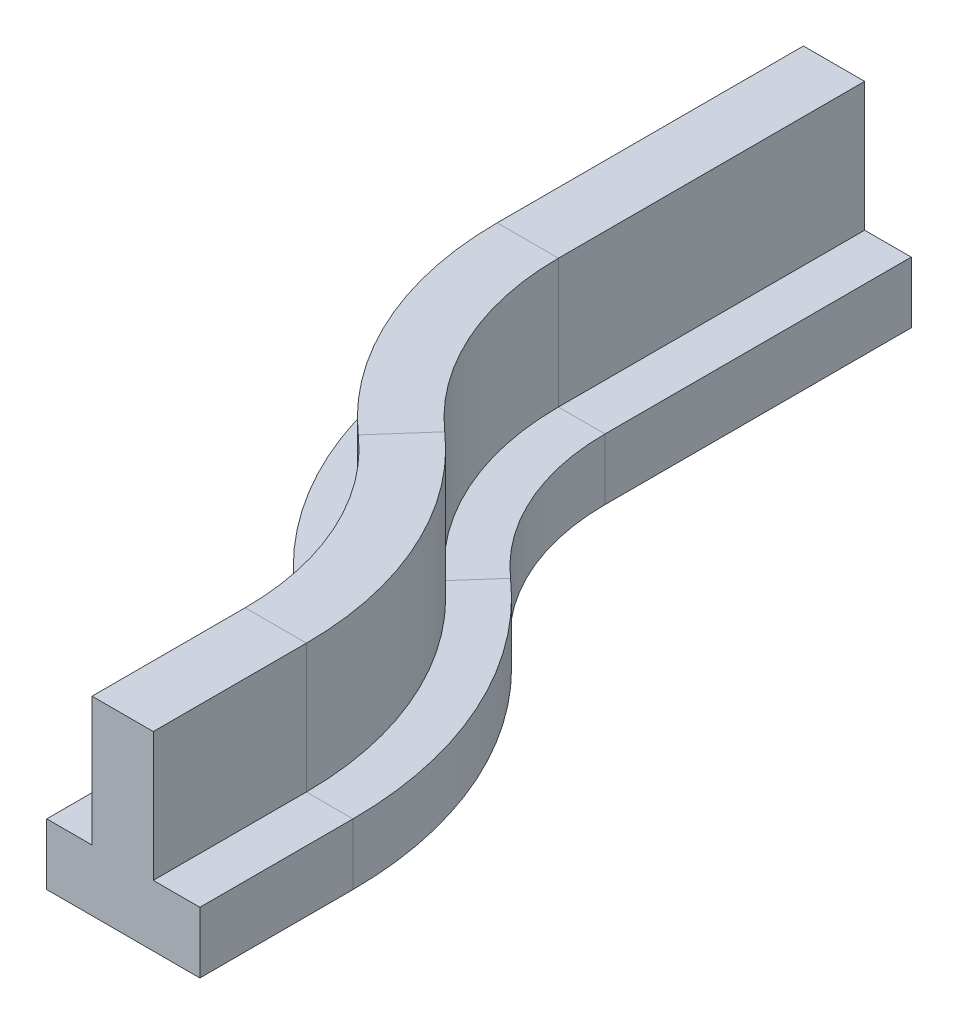
SolidWorks part; units mm, degrees
ref_plane "Front Plane" through (0, 0, 0) normal (0, 0, 1) x (1, 0, 0)
ref_plane "Top Plane" through (0, 0, 0) normal (0, 1, 0) x (1, 0, 0)
ref_plane "Right Plane" through (0, 0, 0) normal (1, 0, 0) x (0, 0, -1)
sketch "Sketch1" plane through (0, 0, 0) normal (0, 0, 1) x (1, 0, 0)
  line L0 (17.3944, 10) -> (25, 10)
  line L1 (0, 0) -> (25, 0)
  line L2 (0, 0) -> (0, 10)
  line L3 (0, 10) -> (7.3944, 10)
  line L4 (25, 0) -> (25, 10)
  line L5 (7.3944, 31.0446) -> (17.3944, 31.0446)
  line L6 (17.3944, 31.0446) -> (17.3944, 10)
  line L9 (7.3944, 31.0446) -> (7.3944, 10)
  dimension "D1" = 25
  dimension "D2" = 10
sketch "Sketch3" plane through (0, 0, 0) normal (0, 1, 0) x (1, 0, 0)
  line L0 (12.5, 0) -> (12.5, 25)
  line L1 (-21.3562, 100) -> (-21.3562, 150)
  line L2 (0, 0) -> (25, 0) construction
  arc A0 (12.5, 25) -> (-4.4281, 62.5) centre (-37.5, 25) ccw
  arc A1 (-4.4281, 62.5) -> (-21.3562, 100) centre (28.6438, 100) cw
  dimension "D1" = 50
  dimension "D2" = 50
  dimension "D3" = 150
  dimension "D4" = 25
sweep "Sweep1" add profiles "Sketch1" path "Sketch3"
